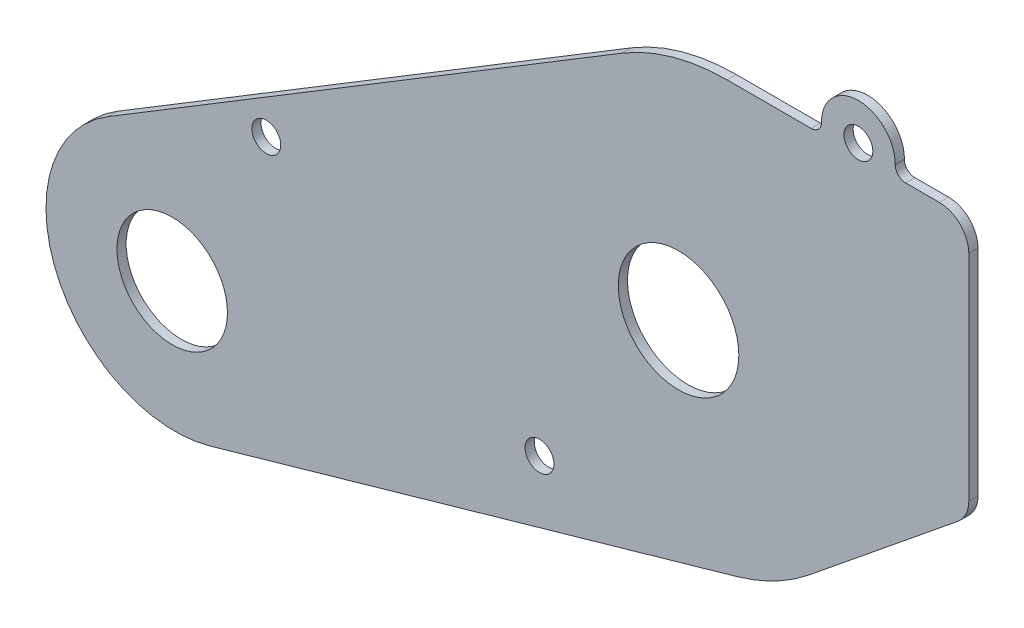
SolidWorks part; units mm, degrees
material "ABS PC"
ref_plane "Front Plane" through (0, 0, 0) normal (0, 0, 1) x (1, 0, 0)
ref_plane "Top Plane" through (0, 0, 0) normal (0, 1, 0) x (1, 0, 0)
ref_plane "Right Plane" through (0, 0, 0) normal (1, 0, 0) x (0, 0, -1)
sketch "Sketch2" plane through (0, 0, 0) normal (0, 0, 1) x (1, 0, 0)
  line L0 (25.0911, -52.0924) -> (-65.6838, -78.0001)
  line L1 (-83.3142, -37.6288) -> (5.2713, 16.1338)
  line L2 (52.3571, 23.0853) -> (52.3571, 22.9801)
  line L3 (-59.5064, -69.3804) -> (-85.0103, -43.8765) construction
  line L5 (63.1592, -24.8058) -> (37.5195, -45.6224)
  line L7 (39.6571, 23.0853) -> (39.6571, 22.9801)
  line L8 (54.1351, 21.2021) -> (59.9573, 21.2021)
  line L10 (65.831, 16.0128) -> (55.9968, 5.3253) construction
  line L11 (42.2751, -9.5867) -> (65.831, 16.0128) construction
  line L12 (65.831, 16.0128) -> (65.831, 22.3186) construction
  line L14 (37.8791, 21.2021) -> (23.3913, 21.2021)
  line L15 (65.0373, 16.1221) -> (65.0373, -20.8619)
  arc A3 (37.5195, -45.6224) -> (25.0911, -52.0924) centre (15.506, -18.5085) cw
  arc A4 (-83.3142, -37.6288) -> (-65.6838, -78.0001) centre (-71.7833, -56.6285) ccw
  circle A8 centre (15.0168, -18.8746) radius 10.3877
  circle A9 centre (-72.2583, -56.6285) radius 9.525
  arc A12 (59.9573, 21.2021) -> (65.0373, 16.1221) centre (59.9573, 16.1221) cw
  arc A13 (63.1592, -24.8058) -> (65.0373, -20.8619) centre (59.9573, -20.8619) ccw
  arc A14 (5.2713, 16.1338) -> (23.3913, 21.2021) centre (23.3913, -13.7229) cw
  arc A16 (52.3571, 23.0853) -> (39.6571, 23.0853) centre (46.0071, 23.0853) ccw
  arc A17 (52.3571, 22.9801) -> (54.1351, 21.2021) centre (54.1351, 22.9801) ccw
  arc A18 (39.6571, 22.9801) -> (37.8791, 21.2021) centre (37.8791, 22.9801) cw
  point P19 (-72.2583, -56.6285)
  point P20 (15.506, -18.5085)
  point P36 (52.3571, 21.2021)
  dimension "D1" = 5.08
  dimension "D2" = 5.08
  dimension "D4" = 1.778
  dimension "D3" = 34.925
extrude "Boss-Extrude1" add sketch "Sketch2" along normal blind 1.5875
sketch "Sketch4" plane through (0, 0, 1.5875) normal (0, 0, 1) x (1, 0, 0)
  line L0 (-58.677, -22.6764) -> (-56.0414, -27.0192) construction
  line L1 (5.2713, 16.1338) -> (-83.3142, -37.6288) construction
  line L2 (-6.9135, -55.744) -> (-8.9513, -51.0906) construction
  line L3 (-62.0382, -79.8833) -> (25.1671, -41.6958) construction
  circle A1 centre (-56.0414, -27.0192) radius 3.9687 construction
  circle A2 centre (-8.9513, -51.0906) radius 3.9687 construction
  point P15 (46.0071, 23.0853)
hole_wizard "#10 Clearance Hole1" positions "Sketch5" profile "Sketch6" hole size "#10" standard "ANSI Inch" end condition through all
sketch "Sketch5" plane through (0, 0, 1.5875) normal (0, 0, 1) x (1, 0, 0)
  point P0 (-56.0414, -27.0192)
  point P3 (-8.9513, -51.0906)
  point P6 (46.0071, 23.0853)
sketch "Sketch6" plane through (-56.0414, -27.0192, 1.5875) normal (1, 0, 0) x (0, -1, 0)
  line L0 (0, 0) -> (0, 1.5875)
  line L1 (0, 1.5875) -> (2.4892, 1.5875)
  line L2 (2.4892, 1.5875) -> (2.4892, 0)
  line L5 (2.4892, 0) -> (0, 0)
  line L11 (0, -6.35) -> (0, 107.95) construction
  dimension "Thru Hole Dia." = 4.9784
  dimension "Thru Hole Depth" = 1.5875
